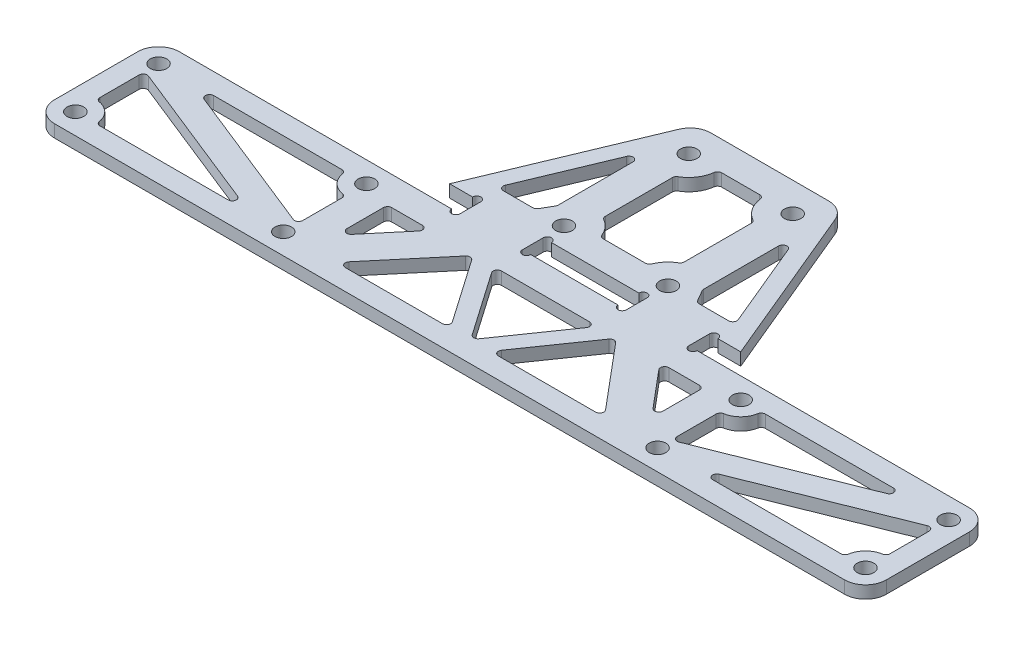
SolidWorks part; units mm, degrees
material "Thornel Mat VMA"
ref_plane "前视基准面" through (0, 0, 0) normal (0, 0, 1) x (1, 0, 0)
ref_plane "上视基准面" through (0, 0, 0) normal (0, 1, 0) x (1, 0, 0)
ref_plane "右视基准面" through (0, 0, 0) normal (1, 0, 0) x (0, 0, -1)
sketch "草图1" plane through (0, 0, 0) normal (0, 1, 0) x (1, 0, 0)
  line L1 (0, 0) -> (25, 0) construction
  line L2 (0, 0) -> (0, 30) construction
  line L3 (0, 30) -> (25, 30) construction
  line L5 (-5, 37) -> (30, 37)
  line L7 (-17, -10) -> (-87.5, -10)
  line L8 (-87.5, -10) -> (-87.5, -40)
  line L9 (-87.5, -40) -> (112.5, -40)
  line L10 (12.5, 37) -> (12.5, -40) construction
  line L11 (112.5, -10) -> (112.5, -40)
  line L12 (42, -10) -> (112.5, -10)
  line L13 (57.5, -15) -> (57.5, -35) construction
  line L14 (-82.5, -15) -> (-32.5, -15) construction
  line L15 (-82.5, -15) -> (-82.5, -35) construction
  line L16 (-82.5, -35) -> (-32.5, -35) construction
  line L17 (-32.5, -15) -> (-32.5, -35) construction
  line L18 (107.5, -35) -> (57.5, -35) construction
  line L19 (107.5, -15) -> (107.5, -35) construction
  line L20 (107.5, -15) -> (57.5, -15) construction
  line L21 (25, 0) -> (25, 30) construction
  line L22 (2, -10) -> (23, -10)
  line L23 (0, -10) -> (0, -5)
  line L24 (2, -5) -> (23, -5)
  line L25 (25, -10) -> (25, -5)
  line L26 (-15, -10) -> (-15, -5)
  line L27 (-17, -5) -> (-22.5, -5)
  line L28 (-22.5, -5) -> (-5, 37)
  line L29 (40, -10) -> (40, -5)
  line L30 (42, -5) -> (47.5, -5)
  line L31 (47.5, -5) -> (30, 37)
  circle A0 centre (0, 30) radius 2
  circle A2 centre (0, 0) radius 2
  circle A4 centre (-82.5, -15) radius 2
  circle A5 centre (-32.5, -15) radius 2
  circle A6 centre (-82.5, -35) radius 2
  circle A7 centre (-32.5, -35) radius 2
  circle A8 centre (57.5, -35) radius 2
  circle A9 centre (107.5, -35) radius 2
  circle A10 centre (57.5, -15) radius 2
  circle A11 centre (107.5, -15) radius 2
  circle A12 centre (25, 0) radius 2
  circle A13 centre (25, 30) radius 2
  arc A14 (0, -5) -> (2, -5) centre (1, -5) cw
  arc A15 (0, -10) -> (2, -10) centre (1, -10) ccw
  arc A16 (25, -10) -> (23, -10) centre (24, -10) cw
  arc A17 (25, -5) -> (23, -5) centre (24, -5) ccw
  arc A18 (-15, -10) -> (-17, -10) centre (-16, -10) cw
  arc A19 (-15, -5) -> (-17, -5) centre (-16, -5) ccw
  arc A20 (40, -10) -> (42, -10) centre (41, -10) ccw
  arc A21 (40, -5) -> (42, -5) centre (41, -5) cw
  dimension "D3" = 4
  dimension "D10" = 4
  dimension "D6" = 35
  dimension "D7" = 1
  dimension "D18" = 1
  dimension "D1" = 30
  dimension "D2" = 25
  dimension "D4" = 7
  dimension "D5" = 10
  dimension "D8" = 30
  dimension "D9" = 200
  dimension "D11" = 5
  dimension "D12" = 5
  dimension "D13" = 5
  dimension "D14" = 50
  dimension "D15" = 25
  dimension "D16" = 5
  dimension "D17" = 55
  dimension "D19" = 70
extrude "凸台-拉伸1" add sketch "草图1" along normal blind 3
fillet "圆角1" radius 5 6 edges at (30, 1.5, -37) (-5, 1.5, -37) (112.5, 1.5, 40) (112.5, 1.5, 10) (-87.5, 1.5, 40) (-87.5, 1.5, 10)
sketch "草图2" plane through (0, 3, 0) normal (0, 1, 0) x (1, 0, 0)
  line L0 (-82.5, -29.0839) -> (-82.5, -19.7081)
  line L1 (-81.1286, -18.7797) -> (-45.3989, -33.0715)
  line L2 (-45.7703, -35) -> (-76.5839, -35)
  line L3 (-82.5, -40) -> (107.5, -40) construction
  line L4 (-87.5, -15) -> (-87.5, -35) construction
  line L5 (-82.5, -15) -> (-32.5, -35) construction
  line L9 (-38.4161, -15) -> (-69.2297, -15)
  line L10 (-69.6011, -16.9285) -> (-33.8714, -31.2203)
  line L11 (-32.5, -30.2919) -> (-32.5, -20.9161)
  line L12 (-17, -10) -> (-82.5, -10) construction
  line L13 (12.5, 37) -> (12.5, -40) construction
  line L14 (26.6667, 37) -> (-1.6667, 37) construction
  line L15 (107.5, -15) -> (57.5, -35) construction
  line L16 (57.5, -30.2919) -> (57.5, -20.9161)
  line L17 (94.6011, -16.9285) -> (58.8714, -31.2203)
  line L18 (63.4161, -15) -> (94.2297, -15)
  line L19 (70.7703, -35) -> (101.5839, -35)
  line L20 (106.1286, -18.7797) -> (70.3989, -33.0715)
  line L21 (107.5, -29.0839) -> (107.5, -19.7081)
  line L22 (-14.5833, 0) -> (-7.5056, 0)
  line L23 (-5, 3.6077) -> (-5, 21.6)
  line L24 (-6.9231, 21.9846) -> (-15.5064, 1.3846)
  line L25 (-6.2821, 33.9231) -> (-22.5, -5) construction
  line L26 (-5.134, 3.1077) -> (-6.6395, 0.5)
  line L27 (30, 3.6077) -> (30, 21.6)
  line L28 (39.5833, 0) -> (32.5056, 0)
  line L29 (31.9231, 21.9846) -> (40.5064, 1.3846)
  line L30 (3, 23.0718) -> (3, 6.9282)
  line L31 (22, 23.0718) -> (22, 6.9282)
  line L32 (7.9373, 30) -> (17.0627, 30)
  line L33 (7.4162, 2) -> (17.5838, 2)
  line L34 (30.134, 3.1077) -> (31.6395, 0.5)
  line L35 (1.9119, -16.9285) -> (23.0881, -16.9285)
  line L37 (11.6786, -33.7457) -> (1.0906, -18.4989)
  line L38 (13.3214, -33.7457) -> (23.9094, -18.4989)
  line L39 (-25.5, -17.9285) -> (-25.5, -26.6833)
  line L40 (-23.7343, -27.3264) -> (-16.3803, -18.5717)
  line L41 (-17.146, -16.9285) -> (-24.5, -16.9285)
  line L42 (-18.3519, -33.3568) -> (-5.5672, -18.1369)
  line L43 (-3.9801, -18.2097) -> (6.5892, -33.4296)
  line L44 (5.7678, -35) -> (-17.5862, -35)
  line L45 (-15, -5) -> (-15, -10) construction
  line L46 (28.9801, -18.2097) -> (18.4108, -33.4296)
  line L47 (43.3519, -33.3568) -> (30.5672, -18.1369)
  line L48 (19.2322, -35) -> (42.5862, -35)
  line L49 (48.7343, -27.3264) -> (41.3803, -18.5717)
  line L50 (50.5, -17.9285) -> (50.5, -26.6833)
  line L51 (42.146, -16.9285) -> (49.5, -16.9285)
  line L52 (23, -5) -> (2, -5) construction
  arc A0 (-81.6667, -30.0699) -> (-77.5699, -34.1667) centre (-82.5, -35) cw
  circle A1 centre (-82.5, -15) radius 2 construction
  circle A2 centre (-32.5, -35) radius 2 construction
  arc A3 (-81.6667, -30.0699) -> (-82.5, -29.0839) centre (-81.5, -29.0839) cw
  arc A4 (-77.5699, -34.1667) -> (-76.5839, -35) centre (-76.5839, -34) ccw
  arc A5 (-45.3989, -33.0715) -> (-45.7703, -35) centre (-45.7703, -34) cw
  arc A6 (-82.5, -19.7081) -> (-81.1286, -18.7797) centre (-81.5, -19.7081) cw
  arc A12 (-37.4301, -15.8333) -> (-38.4161, -15) centre (-38.4161, -16) ccw
  arc A13 (-33.3333, -19.9301) -> (-32.5, -20.9161) centre (-33.5, -20.9161) cw
  arc A14 (-37.4301, -15.8333) -> (-33.3333, -19.9301) centre (-32.5, -15) ccw
  arc A15 (-33.8714, -31.2203) -> (-32.5, -30.2919) centre (-33.5, -30.2919) ccw
  arc A16 (-69.2297, -15) -> (-69.6011, -16.9285) centre (-69.2297, -16) ccw
  arc A17 (94.2297, -15) -> (94.6011, -16.9285) centre (94.2297, -16) cw
  arc A18 (58.8714, -31.2203) -> (57.5, -30.2919) centre (58.5, -30.2919) cw
  arc A19 (62.4301, -15.8333) -> (58.3333, -19.9301) centre (57.5, -15) cw
  arc A20 (58.3333, -19.9301) -> (57.5, -20.9161) centre (58.5, -20.9161) ccw
  arc A21 (62.4301, -15.8333) -> (63.4161, -15) centre (63.4161, -16) cw
  arc A22 (107.5, -19.7081) -> (106.1286, -18.7797) centre (106.5, -19.7081) ccw
  arc A23 (70.3989, -33.0715) -> (70.7703, -35) centre (70.7703, -34) ccw
  arc A24 (102.5699, -34.1667) -> (101.5839, -35) centre (101.5839, -34) cw
  arc A25 (106.6667, -30.0699) -> (107.5, -29.0839) centre (106.5, -29.0839) ccw
  arc A26 (106.6667, -30.0699) -> (102.5699, -34.1667) centre (107.5, -35) ccw
  circle A27 centre (0, 30) radius 2 construction
  arc A28 (-14.5833, 0) -> (-15.5064, 1.3846) centre (-14.5833, 1) cw
  arc A30 (-5, 21.6) -> (-6.9231, 21.9846) centre (-6, 21.6) ccw
  arc A32 (39.5833, 0) -> (40.5064, 1.3846) centre (39.5833, 1) ccw
  arc A33 (30, 21.6) -> (31.9231, 21.9846) centre (31, 21.6) cw
  arc A34 (3.5, 6.0622) -> (6.4892, 2.625) centre (0, 0) cw
  arc A35 (3.5, 23.9378) -> (6.9451, 29.125) centre (0, 30) ccw
  arc A36 (21.5, 6.0622) -> (18.5108, 2.625) centre (25, 0) ccw
  arc A37 (21.5, 23.9378) -> (18.0549, 29.125) centre (25, 30) cw
  arc A38 (18.0549, 29.125) -> (17.0627, 30) centre (17.0627, 29) ccw
  arc A39 (21.5, 23.9378) -> (22, 23.0718) centre (21, 23.0718) cw
  arc A40 (21.5, 6.0622) -> (22, 6.9282) centre (21, 6.9282) ccw
  arc A41 (18.5108, 2.625) -> (17.5838, 2) centre (17.5838, 3) cw
  arc A42 (6.4892, 2.625) -> (7.4162, 2) centre (7.4162, 3) ccw
  arc A43 (3, 6.9282) -> (3.5, 6.0622) centre (4, 6.9282) ccw
  arc A44 (3, 23.0718) -> (3.5, 23.9378) centre (4, 23.0718) cw
  arc A45 (6.9451, 29.125) -> (7.9373, 30) centre (7.9373, 29) cw
  arc A46 (31.6395, 0.5) -> (32.5056, 0) centre (32.5056, 1) ccw
  arc A47 (30, 3.6077) -> (30.134, 3.1077) centre (31, 3.6077) ccw
  arc A48 (-7.5056, 0) -> (-6.6395, 0.5) centre (-7.5056, 1) ccw
  arc A49 (-5, 3.6077) -> (-5.134, 3.1077) centre (-6, 3.6077) cw
  arc A50 (23.0881, -16.9285) -> (23.9094, -18.4989) centre (23.0881, -17.9285) cw
  arc A51 (13.3214, -33.7457) -> (11.6786, -33.7457) centre (12.5, -33.1753) cw
  arc A52 (1.9119, -16.9285) -> (1.0906, -18.4989) centre (1.9119, -17.9285) ccw
  arc A53 (6.5892, -33.4296) -> (5.7678, -35) centre (5.7678, -34) cw
  arc A54 (-5.5672, -18.1369) -> (-3.9801, -18.2097) centre (-4.8015, -18.7801) cw
  arc A55 (-18.3519, -33.3568) -> (-17.5862, -35) centre (-17.5862, -34) ccw
  arc A56 (-25.5, -26.6833) -> (-23.7343, -27.3264) centre (-24.5, -26.6833) ccw
  arc A57 (-16.3803, -18.5717) -> (-17.146, -16.9285) centre (-17.146, -17.9285) ccw
  arc A58 (-25.5, -17.9285) -> (-24.5, -16.9285) centre (-24.5, -17.9285) cw
  arc A59 (30.5672, -18.1369) -> (28.9801, -18.2097) centre (29.8015, -18.7801) ccw
  arc A60 (18.4108, -33.4296) -> (19.2322, -35) centre (19.2322, -34) ccw
  arc A61 (43.3519, -33.3568) -> (42.5862, -35) centre (42.5862, -34) cw
  arc A62 (50.5, -26.6833) -> (48.7343, -27.3264) centre (49.5, -26.6833) cw
  arc A63 (41.3803, -18.5717) -> (42.146, -16.9285) centre (42.146, -17.9285) cw
  arc A64 (50.5, -17.9285) -> (49.5, -16.9285) centre (49.5, -17.9285) ccw
  point P111 (31.9282, 0)
  point P114 (18, 30)
  point P117 (22, 23.6754)
  point P120 (22, 6.3246)
  point P123 (18.2918, 2)
  point P126 (6.7082, 2)
  point P129 (3, 6.3246)
  point P132 (3, 23.6754)
  point P135 (7, 30)
  point P138 (30, 3.3397)
  point P141 (-6.9282, 0)
  point P144 (-5, 3.3397)
  point P162 (25, -16.9285)
  point P165 (12.5, -34.9285)
  point P168 (0, -16.9285)
  point P177 (-25.5, -29.4285)
  point P180 (-15, -16.9285)
  point P183 (-25.5, -16.9285)
  dimension "D1" = 5
  dimension "D3" = 5
  dimension "D6" = 1
  dimension "D7" = 3
  dimension "D10" = 1
  dimension "D12" = 1
  dimension "D13" = 7
  dimension "D15" = 1
  dimension "D18" = 1
  dimension "D26" = 1
  dimension "D2" = 5
  dimension "D4" = 3
  dimension "D5" = 3
  dimension "D8" = 5
  dimension "D9" = 4
  dimension "D11" = 5
  dimension "D14" = 3
  dimension "D16" = 6
  dimension "D17" = 120
  dimension "D19" = 25
  dimension "D20" = 18
  dimension "D21" = 7
  dimension "D22" = 12.5
  dimension "D23" = 5
  dimension "D24" = 8
  dimension "D25" = 4
  dimension "D27" = 7
extrude "切除-拉伸1" cut sketch "草图2" against normal through all
